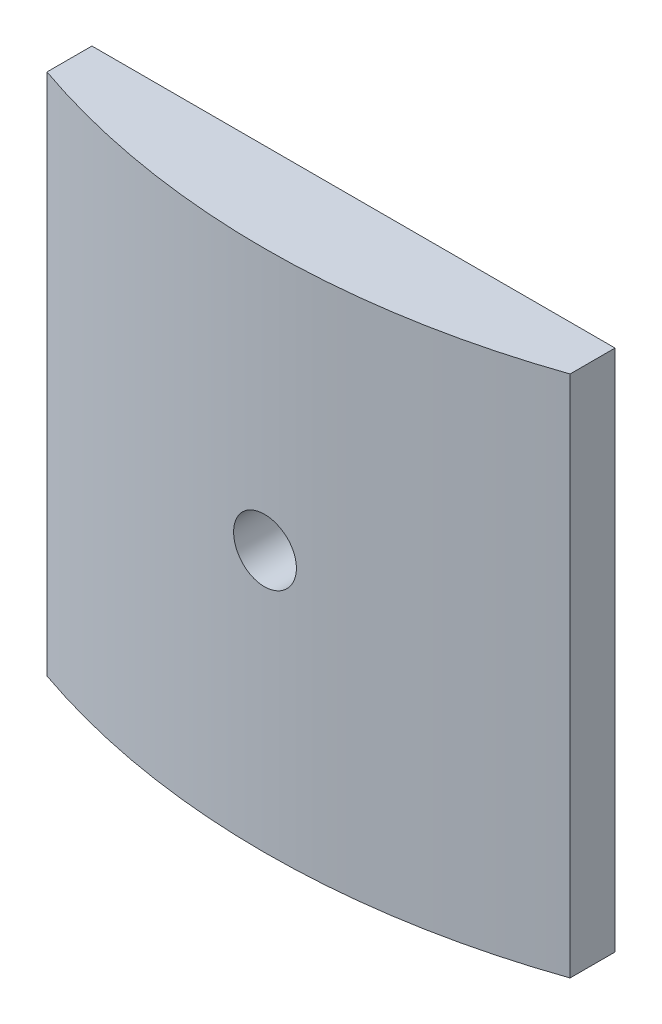
SolidWorks part; units mm, degrees
material "ABS"
ref_plane "Front Plane" through (0, 0, 0) normal (0, 0, 1) x (1, 0, 0)
ref_plane "Top Plane" through (0, 0, 0) normal (0, 1, 0) x (1, 0, 0)
ref_plane "Right Plane" through (0, 0, 0) normal (1, 0, 0) x (0, 0, -1)
sketch "Sketch2" plane through (0, 0, 0) normal (0, 1, 0) x (1, 0, 0)
  line L1 (-17.5, -33.8432) -> (17.5, -33.8432) construction
  line L2 (0, 0) -> (0, -60.5871) construction
  line L3 (0, -33.8432) -> (-12.5, -33.8432)
  line L4 (0, -33.8432) -> (12.5, -33.8432)
  line L7 (-12.5, -33.8432) -> (-12.5, -35.9911)
  line L8 (12.5, -33.8432) -> (12.5, -35.9911)
  circle A2 centre (0, 0) radius 38.1 construction
  arc A3 (-12.5, -35.9911) -> (12.5, -35.9911) centre (0, 0) ccw
  point P11 (0, -38.1)
  point P12 (0, -33.8432)
  dimension "D5" = 76.2
  dimension "D2" = 35
  dimension "D3" = 12.5
  dimension "D4" = 12.5
extrude "Boss-Extrude1" add sketch "Sketch2" along normal blind 25 contours L3 L7 A3 L8 L4
sketch "Sketch3" plane through (0, 0, 33.8432) normal (0, 0, -1) x (-1, 0, 0)
  line L0 (-12.5, 0) -> (12.5, 25) construction
  line L1 (-12.5, 25) -> (12.5, 0) construction
  circle A0 centre (0, 12.5) radius 1.5
  dimension "D1" = 3
extrude "Cut-Extrude1" cut sketch "Sketch3" against normal blind 20
